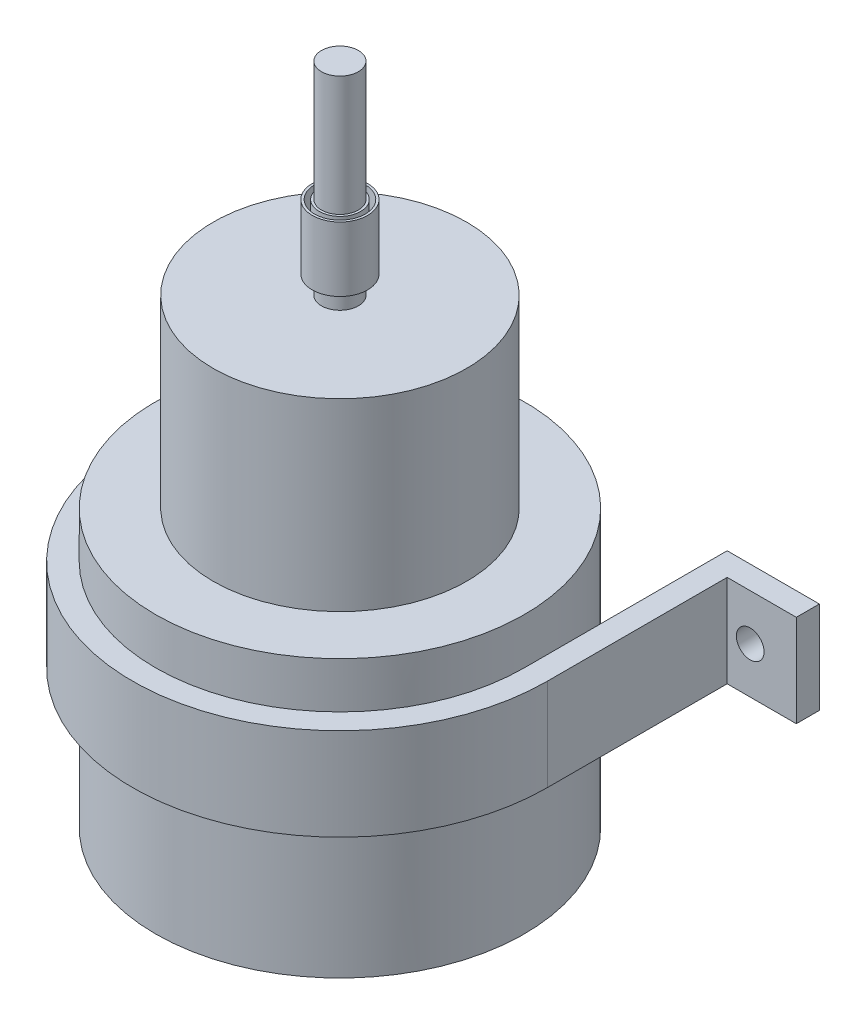
SolidWorks part; units mm, degrees
ref_plane "Front Plane" through (0, 0, 0) normal (0, 0, 1) x (1, 0, 0)
ref_plane "Top Plane" through (0, 0, 0) normal (0, 1, 0) x (1, 0, 0)
ref_plane "Right Plane" through (0, 0, 0) normal (1, 0, 0) x (0, 0, -1)
sketch "Sketch1" plane through (0, 0, 0) normal (0, 1, 0) x (1, 0, 0)
  circle A0 centre (0, 0) radius 20
  dimension "D1" = 40
extrude "Boss-Extrude1" add sketch "Sketch1" along normal blind 30
sketch "Sketch2" plane through (0, 30, 0) normal (0, 1, 0) x (1, 0, 0)
  circle A0 centre (0, 0) radius 13.75
  dimension "D1" = 27.5
extrude "Boss-Extrude2" add sketch "Sketch2" along normal blind 20
sketch "Sketch3" plane through (0, 50, 0) normal (0, 1, 0) x (1, 0, 0)
  circle A0 centre (0, 0) radius 2
  dimension "D1" = 4
extrude "Boss-Extrude3" add sketch "Sketch3" along normal blind 22
ref_plane "Plane1" through (0, 25, 0) normal (0, 1, 0) x (1, 0, 0)
sketch "Sketch4" plane through (0, 25, 0) normal (0, 1, 0) x (1, 0, 0)
  line L0 (-20, 0) -> (-20, 22)
  line L1 (-20, 22) -> (-30, 22)
  line L2 (0, -22) -> (0, 22) construction
  line L3 (20, 0) -> (20, 22)
  line L4 (20, 22) -> (30, 22)
  arc A0 (-20, 0) -> (20, 0) centre (0, 0) ccw
  dimension "D1" = 22
  dimension "D2" = 10
extrude "Extrude-Thin2" add sketch "Sketch4" against normal blind 10 thin thin type one direction wall 2.5
sketch "Sketch6" plane through (0, 0, -22) normal (0, 0, -1) x (-1, 0, 0)
  line L2 (-30, 15) -> (-30, 25) construction
  line L3 (24.475, 25) -> (-24.475, 25) construction
  line L4 (0, 22) -> (0, -22) construction
  circle A0 centre (-25, 20) radius 1.5
  circle A1 centre (25, 20) radius 1.5
  dimension "D1" = 3
  dimension "D2" = 5
  dimension "D3" = 5
extrude "Cut-Extrude1" cut sketch "Sketch6" against normal blind 10
ref_plane "Plane5" through (0, 52, 0) normal (0, 1, 0) x (1, 0, 0)
sketch "Sketch7" plane through (0, 52, 0) normal (0, 1, 0) x (1, 0, 0)
  circle A0 centre (0, 0) radius 2
  circle A1 centre (0, 0) radius 2.25
  circle A2 centre (0, 0) radius 2.75
  circle A3 centre (0, 0) radius 3
  dimension "D1" = 4
  dimension "D2" = 4.5
  dimension "D3" = 5.5
  dimension "D4" = 6
extrude "Boss-Extrude4" add sketch "Sketch7" along normal blind 7 contours A1 A0 | A3 A2
